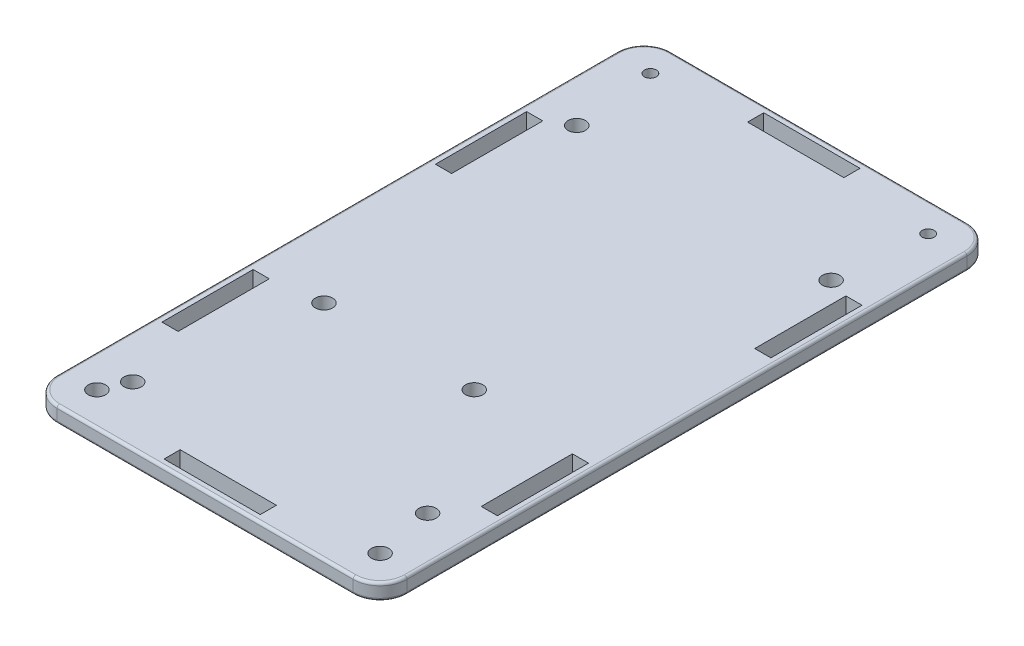
SolidWorks part; units mm, degrees
ref_plane "Front Plane" through (0, 0, 0) normal (0, 0, 1) x (1, 0, 0)
ref_plane "Top Plane" through (0, 0, 0) normal (0, 1, 0) x (1, 0, 0)
ref_plane "Right Plane" through (0, 0, 0) normal (1, 0, 0) x (0, 0, -1)
sketch "Sketch1" plane through (0, 0, 0) normal (0, 1, 0) x (1, 0, 0)
  line L0 (-32.5, -47) -> (-32.5, -52)
  line L1 (-22.5, 57) -> (22.5, 57)
  line L2 (-32.5, 47) -> (-32.5, -47)
  line L3 (-22.5, -57) -> (22.5, -57)
  line L4 (32.5, 47) -> (32.5, -47)
  line L5 (-32.5, 57) -> (32.5, -57) construction
  line L6 (-32.5, -57) -> (32.5, 57) construction
  line L8 (-22.5, -57) -> (-27.5, -57)
  line L9 (32.5, -47) -> (32.5, -52)
  line L10 (27.5, -57) -> (22.5, -57)
  line L11 (32.5, 47) -> (32.5, 52)
  line L12 (27.5, 57) -> (22.5, 57)
  line L13 (-22.5, 57) -> (-27.5, 57)
  line L14 (-32.5, 52) -> (-32.5, 47)
  arc A0 (-27.5, 57) -> (-32.5, 52) centre (-27.5, 52) ccw
  arc A1 (32.5, 52) -> (27.5, 57) centre (27.5, 52) ccw
  arc A2 (32.5, -52) -> (27.5, -57) centre (27.5, -52) cw
  arc A3 (-32.5, -52) -> (-27.5, -57) centre (-27.5, -52) ccw
  point P0 (0, 0)
  dimension "D3" = 5
  dimension "D1" = 114
  dimension "D2" = 65
extrude "Boss-Extrude3" add sketch "Sketch1" along normal blind 3
sketch "Sketch2" plane through (0, 3, 0) normal (0, 1, 0) x (1, 0, 0)
  line L0 (27.5, 57) -> (-27.5, 57) construction
  line L1 (32.5, -52) -> (32.5, 52) construction
  circle A0 centre (24.261, 35.015) radius 1.608
  dimension "D1" = 21.985
  dimension "D2" = 8.239
  dimension "D3" = 3.216
extrude "Cut-Extrude3" cut sketch "Sketch2" against normal blind 3
sketch "Sketch7" plane through (0, 0, 0) normal (0, -1, 0) x (1, 0, 0)
  line L0 (32.5, 52) -> (32.5, -52) construction
  line L1 (-27.5, 57) -> (27.5, 57) construction
  circle A0 centre (24.261, 39.945) radius 1.608
  dimension "D1" = 8.239
  dimension "D2" = 3.216
  dimension "D3" = 17.055
extrude "Cut-Extrude8" cut sketch "Sketch7" against normal blind 3
sketch "Sketch8" plane through (0, 0, 0) normal (0, -1, 0) x (1, 0, 0)
  line L0 (27.5, -57) -> (-27.5, -57) construction
  line L1 (-32.5, -52) -> (-32.5, 52) construction
  circle A0 centre (-24.261, -36.285) radius 1.608
  dimension "D1" = 3.216
  dimension "D2" = 20.715
  dimension "D3" = 8.239
extrude "Cut-Extrude9" cut sketch "Sketch8" against normal blind 3
sketch "Sketch9" plane through (0, 0, 0) normal (0, -1, 0) x (1, 0, 0)
  line L0 (-32.5, -52) -> (-32.5, 52) construction
  circle A0 centre (-19.183, 15.745) radius 1.608
  circle A1 centre (-24.261, -36.285) radius 1.608 construction
  circle A2 centre (8.726, 15.746) radius 1.608
  circle A3 centre (24.261, -35.015) radius 1.608 construction
  circle A4 centre (-24.261, 46.193) radius 1.608
  dimension "D1" = 3.216
  dimension "D2" = 52.03
  dimension "D3" = 13.317
  dimension "D4" = 3.216
  dimension "D5" = 27.909
  dimension "D6" = 50.761
  dimension "D7" = 82.478
  dimension "D8" = 8.239
  dimension "D9" = 3.216
extrude "Cut-Extrude11" cut sketch "Sketch9" against normal blind 3
sketch "Sketch10" plane through (0, 3, 0) normal (0, 1, 0) x (1, 0, 0)
  line L0 (26.8, 0) -> (30.9923, 0) construction
  line L1 (-26.8, 50.8) -> (26.8, 50.8)
  line L2 (-26.8, 0) -> (-26.8, -50.8)
  line L3 (-26.8, -50.8) -> (26.8, -50.8)
  line L4 (26.8, 50.8) -> (26.8, 0)
  line L5 (-26.8, 50.8) -> (26.8, -50.8) construction
  line L6 (-26.8, -50.8) -> (26.8, 50.8) construction
  line L7 (-26.8, 0) -> (-30.3516, 0) construction
  line L8 (-27.5, -57) -> (27.5, -57) construction
  line L9 (28.15, -16.933) -> (31.15, -16.933)
  line L10 (28.15, -16.933) -> (28.15, -33.866)
  line L11 (28.15, -33.866) -> (31.15, -33.866)
  line L12 (31.15, -16.933) -> (31.15, -33.866)
  line L13 (8.93, -52.7) -> (-8.94, -52.7)
  line L14 (8.93, -52.7) -> (8.93, -55.7)
  line L15 (8.93, -55.7) -> (-8.94, -55.7)
  line L16 (-8.94, -52.7) -> (-8.94, -55.7)
  line L17 (-26.8, 50.8) -> (-26.8, 1.3398) construction
  point P0 (0, 0)
  dimension "D1" = 101.6
  dimension "D2" = 53.6
  dimension "D3" = 16.933
  dimension "D4" = 16.933
  dimension "D5" = 3
  dimension "D6" = 1.35
  dimension "D7" = 17.87
  dimension "D8" = 17.87
  dimension "D9" = 3
  dimension "D10" = 1.3
extrude "Cut-Extrude14" cut sketch "Sketch10" against normal blind 3 contours L13 L16 L15 L14 | L12 L9 L10 L11
mirror "Mirror3" about plane through (0, 0, 0) normal (0, 0, 1) of "Cut-Extrude14"
mirror "Mirror4" about plane through (0, 0, 0) normal (1, 0, 0) of "Mirror3", "Cut-Extrude14"
sketch "Sketch11" plane through (0, 3, 0) normal (0, 1, 0) x (1, 0, 0)
  line L0 (-27.5, -57) -> (27.5, -57) construction
  line L1 (-32.5, 52) -> (-32.5, -52) construction
  circle A0 centre (-26.3, -50.8) radius 1.608
  dimension "D1" = 3.216
  dimension "D2" = 6.2
  dimension "D3" = 6.2
extrude "Cut-Extrude15" cut sketch "Sketch11" against normal blind 3
mirror "Mirror5" about plane through (0, 0, 0) normal (1, 0, 0) of "Cut-Extrude15"
fillet "Fillet1" radius 0.5 8 edges at (31.0355, 0, 55.5355) (0, 0, 57) (-31.0355, 0, 55.5355) (-32.5, 0, 0) (-31.0355, 0, -55.5355) (0, 0, -57) (31.0355, 0, -55.5355) (32.5, 0, 0)
fillet "Fillet2" radius 0.5 8 edges at (31.0355, 3, 55.5355) (0, 3, 57) (-31.0355, 3, 55.5355) (-32.5, 3, 0) (-31.0355, 3, -55.5355) (0, 3, -57) (31.0355, 3, -55.5355) (32.5, 3, 0)
sketch "Sketch12" plane through (0, 3, 0) normal (0, 1, 0) x (1, 0, 0)
  line L0 (32, -52) -> (32, 52) construction
  line L1 (27.5, 56.5) -> (-27.5, 56.5) construction
  circle A0 centre (25.8, 51.5) radius 1.108
  dimension "D1" = 6.2
  dimension "D2" = 5
  dimension "D3" = 2.216
extrude "Cut-Extrude16" cut sketch "Sketch12" against normal blind 3
mirror "Mirror8" about plane through (0, 0, 0) normal (1, 0, 0) of "Cut-Extrude16"
